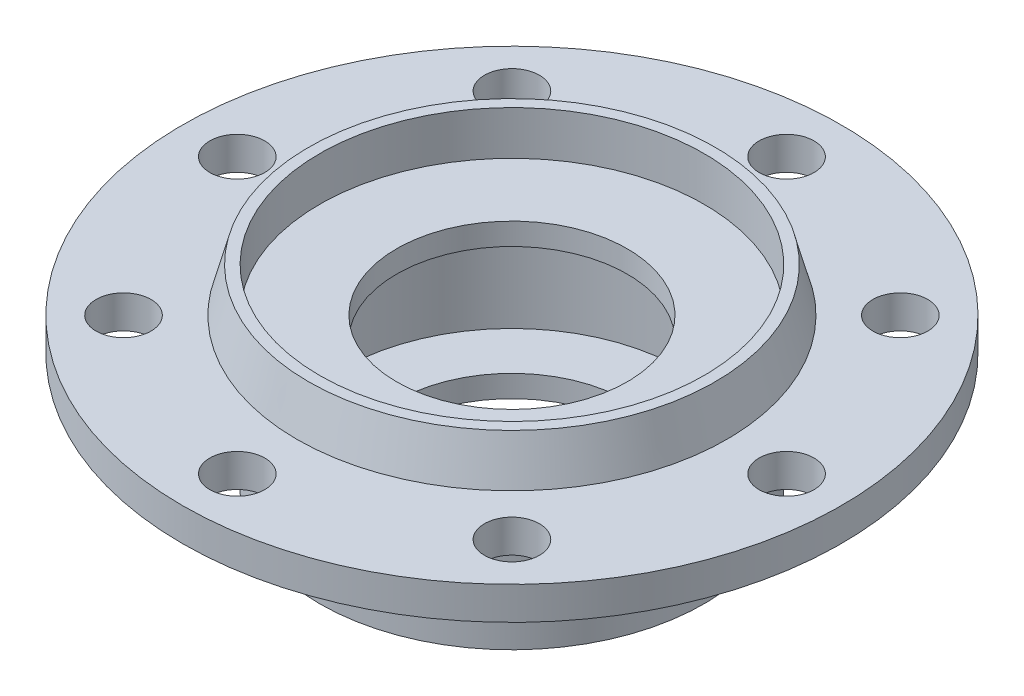
SolidWorks part; units mm, degrees
ref_plane "Front Plane" through (0, 0, 0) normal (0, 0, 1) x (1, 0, 0)
ref_plane "Top Plane" through (0, 0, 0) normal (0, 1, 0) x (1, 0, 0)
ref_plane "Right Plane" through (0, 0, 0) normal (1, 0, 0) x (0, 0, -1)
sketch "Sketch2" plane through (0, 0, 0) normal (0, 0, 1) x (1, 0, 0)
  line L0 (-68.5279, 64.8477) -> (-68.5279, 14.8477) construction
  line L1 (-47.5279, 29.5157) -> (-37.5279, 29.5157)
  line L2 (-37.5279, 29.5157) -> (-37.5279, 49.5157)
  line L3 (-37.5279, 49.5157) -> (-47.5279, 49.5157)
  line L4 (-47.5279, 49.5157) -> (-47.5279, 53.5157)
  line L5 (-47.5279, 53.5157) -> (-33.5279, 53.5157)
  line L6 (-33.5279, 53.5157) -> (-33.5279, 61.5157)
  line L7 (-33.5279, 61.5157) -> (-31.5279, 61.5157)
  line L8 (-31.5279, 61.5157) -> (-29.3843, 53.5157)
  line L9 (-29.3843, 53.5157) -> (-8.5279, 53.5157)
  line L10 (-8.5279, 53.5157) -> (-8.5279, 47.5157)
  line L11 (-8.5279, 47.5157) -> (-33.5279, 47.5157)
  line L12 (-33.5279, 47.5157) -> (-33.5279, 27.4276)
  line L13 (-33.5279, 27.4276) -> (-33.5279, 25.5157)
  line L14 (-33.5279, 25.5157) -> (-47.5279, 25.5157)
  line L15 (-47.5279, 25.5157) -> (-47.5279, 29.5157)
  dimension "D1" = 60
  dimension "D2" = 37
  dimension "D3" = 35
  dimension "D4" = 31
  dimension "D5" = 8
  dimension "D6" = 28
  dimension "D7" = 20
  dimension "D8" = 4
  dimension "D9" = 4
  dimension "D10" = 6
  dimension "D11" = 21
  dimension "D12" = 105
revolve "Revolve1" add sketch "Sketch2" angle 360 about L0
sketch "Sketch3" plane through (0, 53.5157, 0) normal (0, 1, 0) x (1, 0, 0)
  circle A0 centre (-68.5279, 0) radius 50 construction
  circle A1 centre (-118.5279, 0) radius 5
  circle A2 centre (-103.8833, 35.3553) radius 5
  circle A3 centre (-68.5279, 50) radius 5
  circle A4 centre (-33.1726, 35.3553) radius 5
  circle A5 centre (-18.5279, 0) radius 5
  circle A6 centre (-33.1726, -35.3553) radius 5
  circle A7 centre (-68.5279, -50) radius 5
  circle A8 centre (-103.8833, -35.3553) radius 5
  point P21 (-68.5279, 0)
  dimension "D1" = 100
  dimension "D2" = 10
  dimension "D3" = 8
extrude "Cut-Extrude1" cut sketch "Sketch3" against normal blind 10
